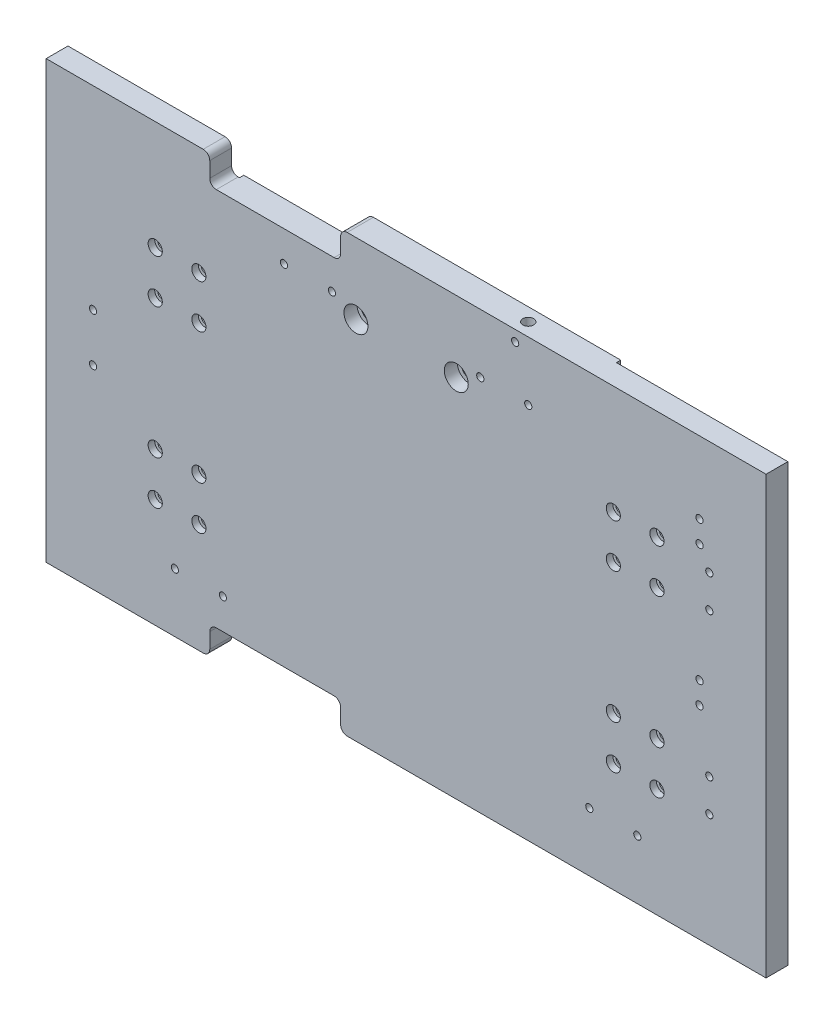
SolidWorks part; units mm, degrees
material "SKD11淬火HRC56-60"
ref_plane "前基準面" through (0, 0, 0) normal (0, 0, 1) x (1, 0, 0)
ref_plane "上基準面" through (0, 0, 0) normal (0, 1, 0) x (1, 0, 0)
ref_plane "右基準面" through (0, 0, 0) normal (1, 0, 0) x (0, 0, -1)
sketch "草图1" plane through (0, 0, 0) normal (0, 0, 1) x (1, 0, 0)
  line L1 (0, 0) -> (330, 0)
  line L2 (0, 0) -> (0, 200)
  line L3 (0, 200) -> (330, 200)
  line L4 (330, 0) -> (330, 200)
  dimension "D1" = 330
  dimension "D2" = 200
extrude "凸台-拉伸1" add sketch "草图1" along normal blind 12
sketch "草图2" plane through (0, 0, 0) normal (0, -1, 0) x (1, 0, 0)
  line L0 (165, 12) -> (165, 0) construction
  line L1 (0, 0) -> (78.6, 0)
  line L2 (0, 0) -> (0, 2)
  line L3 (0, 2) -> (78.6, 2)
  line L4 (78.6, 0) -> (78.6, 2)
  line L5 (0, 12) -> (330, 12) construction
  line L6 (0, 0) -> (330, 0) construction
  line L7 (251.4, 0) -> (251.4, 2)
  line L8 (330, 2) -> (251.4, 2)
  line L9 (330, 0) -> (330, 2)
  line L10 (330, 0) -> (251.4, 0)
  dimension "D1" = 172.8
  dimension "D2" = 2
extrude "切除-拉伸1" cut sketch "草图2" against normal through all
sketch "草图4" plane through (0, 200, 0) normal (0, 1, 0) x (1, 0, 0)
  line L0 (330, -12) -> (0, -12) construction
  line L1 (330, -12) -> (330, -2) construction
  circle A0 centre (215, -6) radius 2.5
  dimension "D1" = 5
  dimension "D2" = 6
  dimension "D3" = 115
extrude "切除-拉伸3" cut sketch "草图4" against normal blind 12
hole_wizard "M4 螺纹孔1" positions "草图6" profile "草图5" tap size "M4" standard "ISO"
sketch "草图6" plane through (0, 0, 12) normal (0, 0, 1) x (1, 0, 0)
  point P0 (109, 173)
  point P4 (131, 173)
  point P7 (199, 173)
  point P10 (221, 173)
  point P13 (21.5, 111)
  point P16 (21.5, 89)
  point P19 (59, 27)
  point P22 (81, 27)
  point P25 (249, 27)
  point P28 (271, 27)
  point P31 (304, 52)
  point P34 (304, 67)
  point P37 (304, 133)
  point P40 (304, 148)
sketch "草图5" plane through (109, 173, 12) normal (1, 0, 0) x (0, -1, 0)
  line L0 (0, 0) -> (0, 11.0914)
  line L1 (0, 11.0914) -> (1.65, 10.1)
  line L2 (1.65, 10.1) -> (1.65, 0)
  line L5 (1.65, 0) -> (0, 0)
  line L10 (0, 11.0914) -> (-1.65, 10.1) construction
  line L11 (0, -6.35) -> (0, 107.95) construction
  dimension "螺纹孔钻头直径" = 3.3
  dimension "螺纹孔钻头深度" = 10.1
  dimension "导头角度" = 118
cosmetic thread "孔螺蚊线1" parameters "D1"=8, "D2"=4
cosmetic thread "孔螺蚊线2" parameters "D1"=8, "D2"=4
cosmetic thread "孔螺蚊线3" parameters "D1"=8, "D2"=4
cosmetic thread "孔螺蚊线4" parameters "D1"=8, "D2"=4
cosmetic thread "孔螺蚊线5" parameters "D1"=8, "D2"=4
cosmetic thread "孔螺蚊线6" parameters "D1"=8, "D2"=4
cosmetic thread "孔螺蚊线7" parameters "D1"=8, "D2"=4
cosmetic thread "孔螺蚊线8" parameters "D1"=8, "D2"=4
cosmetic thread "孔螺蚊线9" parameters "D1"=8, "D2"=4
cosmetic thread "孔螺蚊线10" parameters "D1"=8, "D2"=4
cosmetic thread "孔螺蚊线11" parameters "D1"=8, "D2"=4
cosmetic thread "孔螺蚊线12" parameters "D1"=8, "D2"=4
cosmetic thread "孔螺蚊线13" parameters "D1"=8, "D2"=4
cosmetic thread "孔螺蚊线14" parameters "D1"=8, "D2"=4
hole_wizard "M6 六角凹头螺钉的柱形沉头孔1" positions "草图8" profile "草图7" counterbore size "M6" standard "ISO" end condition through all
sketch "草图8" plane through (0, 0, 12) normal (0, 0, 1) x (1, 0, 0)
  point P0 (188, 167.5)
  point P3 (142, 167.5)
sketch "草图7" plane through (188, 167.5, 12) normal (1, 0, 0) x (0, -1, 0)
  line L0 (0, 0) -> (0, 12)
  line L1 (0, 12) -> (3.5, 12)
  line L3 (3.5, 12) -> (3.5, 6)
  line L4 (3.5, 6) -> (5.5, 6)
  line L5 (5.5, 6) -> (5.5, 0)
  line L7 (5.5, 0) -> (0, 0)
  line L11 (0, -6.35) -> (0, 107.95) construction
  dimension "通孔孔直径" = 7
  dimension "通孔孔深度" = 12
  dimension "柱形沉头孔直径" = 11
  dimension "柱形沉头孔深度" = 6
hole_wizard "M3 六角凹头螺钉的柱形沉头孔1" positions "草图10" profile "草图9" counterbore size "M3" standard "ISO" end condition through all
sketch "草图10" plane through (0, 0, 12) normal (0, 0, 1) x (1, 0, 0)
  point P0 (70, 150)
  point P7 (50, 150)
  point P10 (50, 130)
  point P13 (70, 130)
  point P16 (70, 50)
  point P19 (50, 50)
  point P22 (70, 70)
  point P25 (50, 70)
  point P28 (280, 50)
  point P31 (260, 50)
  point P34 (280, 70)
  point P37 (260, 70)
  point P40 (280, 150)
  point P43 (260, 150)
  point P46 (280, 130)
  point P49 (260, 130)
sketch "草图9" plane through (70, 150, 12) normal (1, 0, 0) x (0, -1, 0)
  line L0 (0, 0) -> (0, 12)
  line L1 (0, 12) -> (1.8, 12)
  line L3 (1.8, 12) -> (1.8, 3)
  line L4 (1.8, 3) -> (3.25, 3)
  line L5 (3.25, 3) -> (3.25, 0)
  line L7 (3.25, 0) -> (0, 0)
  line L11 (0, -6.35) -> (0, 107.95) construction
  dimension "通孔孔直径" = 3.6
  dimension "通孔孔深度" = 12
  dimension "柱形沉头孔直径" = 6.5
  dimension "柱形沉头孔深度" = 3
sketch "草图11" plane through (0, 0, 12) normal (0, 0, 1) x (1, 0, 0)
  line L0 (330, 200) -> (0, 200) construction
  line L1 (135, 200) -> (75, 200)
  line L2 (135, 200) -> (135, 187)
  line L3 (135, 187) -> (75, 187)
  line L4 (75, 200) -> (75, 187)
  line L5 (0, 100) -> (217.0583, 100) construction
  line L6 (0, 200) -> (0, 0) construction
  line L7 (75, 0) -> (75, 13)
  line L8 (135, 13) -> (75, 13)
  line L9 (135, 0) -> (135, 13)
  line L10 (135, 0) -> (75, 0)
  dimension "D1" = 13
  dimension "D2" = 60
  dimension "D3" = 75
extrude "切除-拉伸4" cut sketch "草图11" against normal through all
fillet "圆角1" radius 3 8 edges at (135, 13, 6) (135, 0, 6) (75, 13, 7) (75, 0, 7) (75, 187, 7) (75, 200, 7) (135, 200, 6) (135, 187, 6)
hole_wizard "M4 螺纹孔2" positions "草图13" profile "草图12" tap size "M4" standard "ISO"
sketch "草图13" plane through (0, 0, 12) normal (0, 0, 1) x (1, 0, 0)
  line L0 (330, 200) -> (138, 200) construction
  line L1 (330, 0) -> (330, 200) construction
  point P0 (215, 195)
  dimension "D1" = 5
  dimension "D2" = 115
sketch "草图12" plane through (215, 195, 12) normal (1, 0, 0) x (0, -1, 0)
  line L0 (0, 0) -> (0, 11.0914)
  line L1 (0, 11.0914) -> (1.65, 10.1)
  line L2 (1.65, 10.1) -> (1.65, 0)
  line L5 (1.65, 0) -> (0, 0)
  line L10 (0, 11.0914) -> (-1.65, 10.1) construction
  line L11 (0, -6.35) -> (0, 107.95) construction
  dimension "螺纹孔钻头直径" = 3.3
  dimension "螺纹孔钻头深度" = 10.1
  dimension "导头角度" = 118
cosmetic thread "孔螺蚊线15" parameters "D1"=8, "D2"=4
hole_wizard "M4 螺纹孔4" positions "草图17" profile "草图16" tap size "M4" standard "ISO"
sketch "草图17" plane through (0, 0, 2) normal (0, 0, -1) x (-1, 0, 0)
  line L0 (-330, 200) -> (-330, 0) construction
  line L1 (-330, 200) -> (-251.4, 200) construction
  point P0 (-299.5, 167)
  point P1 (-299.5, 157)
  point P3 (-299.5, 103)
  point P5 (-299.5, 93)
  dimension "D1" = 10
  dimension "D2" = 10
  dimension "D3" = 30.5
  dimension "D4" = 33
  dimension "D5" = 97
sketch "草图16" plane through (299.5, 167, 2) normal (1, 0, 0) x (0, 1, 0)
  line L0 (0, 0) -> (0, 11.0914)
  line L1 (0, 11.0914) -> (1.65, 10.1)
  line L2 (1.65, 10.1) -> (1.65, 0)
  line L5 (1.65, 0) -> (0, 0)
  line L10 (0, 11.0914) -> (-1.65, 10.1) construction
  line L11 (0, -6.35) -> (0, 107.95) construction
  dimension "螺纹孔钻头直径" = 3.3
  dimension "螺纹孔钻头深度" = 10.1
  dimension "导头角度" = 118
cosmetic thread "孔螺蚊线20" parameters "D1"=8, "D2"=4
cosmetic thread "孔螺蚊线21" parameters "D1"=8, "D2"=4
cosmetic thread "孔螺蚊线22" parameters "D1"=8, "D2"=4
cosmetic thread "孔螺蚊线23" parameters "D1"=8, "D2"=4
hole_wizard "M4 螺纹孔5" positions "草图19" profile "草图18" tap size "M4" standard "ISO"
sketch "草图19" plane through (0, 0, 0) normal (0, 0, -1) x (-1, 0, 0)
  line L0 (0, 200) -> (0, 0) construction
  line L1 (-72, 200) -> (0, 200) construction
  point P0 (-89.5, 158)
  point P1 (-89.5, 168)
  point P3 (-89.5, 93)
  point P5 (-89.5, 103)
  dimension "D1" = 10
  dimension "D2" = 10
  dimension "D3" = 55
  dimension "D4" = 89.5
  dimension "D5" = 32
sketch "草图18" plane through (89.5, 158, 0) normal (1, 0, 0) x (0, 1, 0)
  line L0 (0, 0) -> (0, 11.0914)
  line L1 (0, 11.0914) -> (1.65, 10.1)
  line L2 (1.65, 10.1) -> (1.65, 0)
  line L5 (1.65, 0) -> (0, 0)
  line L10 (0, 11.0914) -> (-1.65, 10.1) construction
  line L11 (0, -6.35) -> (0, 107.95) construction
  dimension "螺纹孔钻头直径" = 3.3
  dimension "螺纹孔钻头深度" = 10.1
  dimension "导头角度" = 118
cosmetic thread "孔螺蚊线24" parameters "D1"=8, "D2"=4
cosmetic thread "孔螺蚊线25" parameters "D1"=8, "D2"=4
cosmetic thread "孔螺蚊线26" parameters "D1"=8, "D2"=4
cosmetic thread "孔螺蚊线27" parameters "D1"=8, "D2"=4
